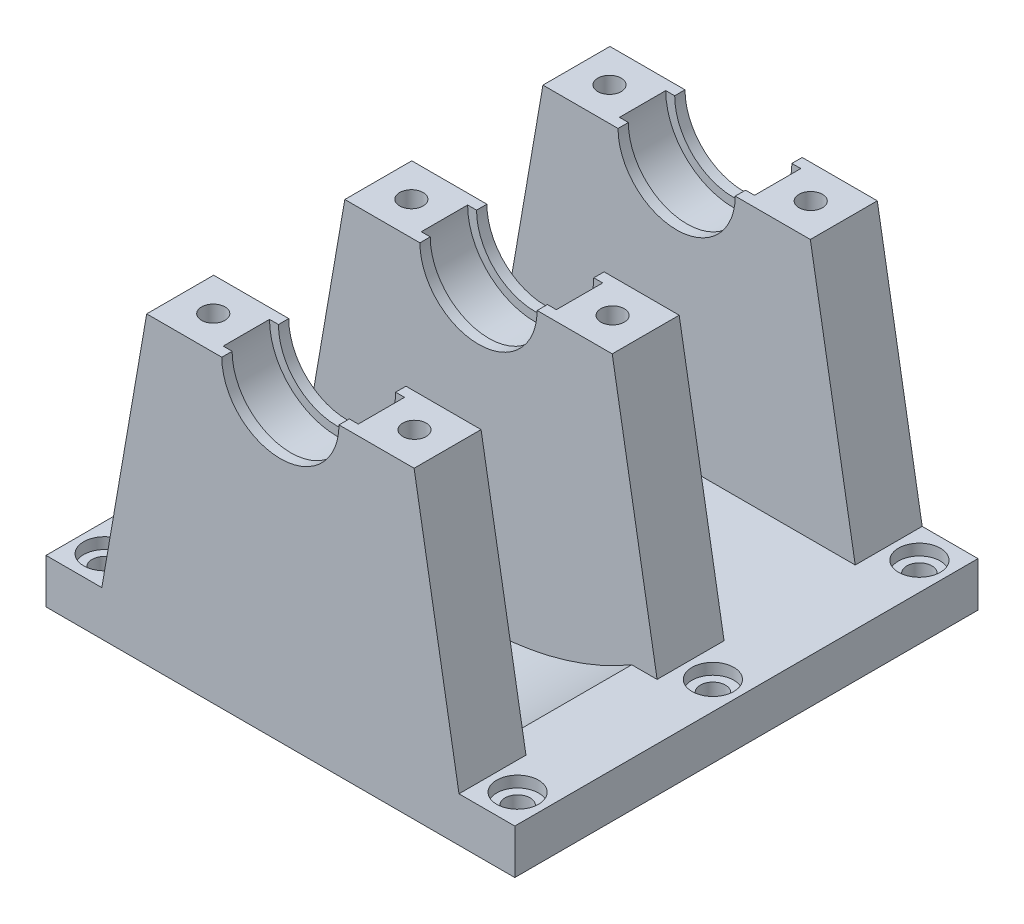
SolidWorks part; units mm, degrees
material "PET"
ref_plane "Piano frontale" through (0, 0, 0) normal (0, 0, 1) x (1, 0, 0)
ref_plane "Piano superiore" through (0, 0, 0) normal (0, 1, 0) x (1, 0, 0)
ref_plane "Piano destro" through (0, 0, 0) normal (1, 0, 0) x (0, 0, -1)
sketch "Schizzo1" plane through (0, 0, 0) normal (0, 0, 1) x (1, 0, 0)
  line L0 (-42, -54.5) -> (42, -54.5)
  line L1 (21, -17.1) -> (-21, -17.1)
  line L2 (21, -17.1) -> (21, 17.1)
  line L3 (21, 17.1) -> (-21, 17.1)
  line L4 (-21, -17.1) -> (-21, 17.1)
  line L5 (21, -17.1) -> (-21, 17.1) construction
  line L6 (21, 17.1) -> (-21, -17.1) construction
  line L7 (-42, -54.5) -> (-42, -46.5)
  line L8 (-42, -46.5) -> (-32, -46.5)
  line L9 (-32, -46.5) -> (-21, 17.1)
  line L10 (42, -54.5) -> (42, -46.5)
  line L11 (42, -46.5) -> (32, -46.5)
  line L12 (32, -46.5) -> (21, 17.1)
  line L13 (-23.9575, 0) -> (23.9575, 0)
  circle A0 centre (0, 0) radius 12.1
  point P9 (0, -54.5)
  dimension "D1" = 24.2
  dimension "D2" = 42
  dimension "D3" = 17.1
  dimension "D4" = 54.5
  dimension "D5" = 84
  dimension "D6" = 8
  dimension "D7" = 10
extrude "Estrusione-Estrusione1" add sketch "Schizzo1" along normal blind 12 contours A0 L13 L4 L1 L2 | L13 L9 L8 L7 L0 L10 L11 L12 L2 L1 L4
sketch "Schizzo2" plane through (0, 0, 12) normal (0, 0, 1) x (1, 0, 0)
  line L0 (-12.1, 0) -> (12.1, 0)
  circle A0 centre (0, 0) radius 10.5
  arc A1 (-12.1, 0) -> (12.1, 0) centre (0, 0) ccw construction
  arc A2 (-12.1, 0) -> (12.1, 0) centre (0, 0) ccw
  arc M11 (12.1, 0) -> (-12.1, 0) centre (0, 0) cw
  dimension "D1" = 21
extrude "Estrusione-Estrusione2" add sketch "Schizzo2" against normal blind 1.85 contours A0 L0 M11
sketch "Schizzo3" plane through (0, 0, 0) normal (0, 0, -1) x (-1, 0, 0)
  line L0 (-12.1, 0) -> (12.1, 0)
  circle A0 centre (0, 0) radius 10.5
  arc A1 (-12.1, 0) -> (12.1, 0) centre (0, 0) ccw construction
  arc A2 (-12.1, 0) -> (12.1, 0) centre (0, 0) ccw
  arc M3 (12.1, 0) -> (-12.1, 0) centre (0, 0) cw
  dimension "D1" = 21
extrude "Estrusione-Estrusione3" add sketch "Schizzo3" against normal blind 1.85 contours A0 L0 M3
sketch "Schizzo4" plane through (0, 0, 0) normal (0, 0, -1) x (-1, 0, 0)
  line L0 (-32, -46.5) -> (32, -46.5)
  line L9 (23.9575, 0) -> (10.5, 0)
  line L10 (-10.5, 0) -> (-23.9575, 0)
  line L11 (-23.9575, 0) -> (-32, -46.5)
  line L12 (-32, -46.5) -> (-42, -46.5)
  line L13 (-42, -46.5) -> (-42, -54.5)
  line L14 (-42, -54.5) -> (42, -54.5)
  line L15 (42, -54.5) -> (42, -46.5)
  line L16 (42, -46.5) -> (32, -46.5)
  line L17 (32, -46.5) -> (23.9575, 0)
  line L18 (23.9575, 0) -> (10.5, 0)
  line L19 (-10.5, 0) -> (-23.9575, 0)
  line L20 (-23.9575, 0) -> (-32, -46.5)
  line L21 (-32, -46.5) -> (-42, -46.5)
  line L22 (-42, -46.5) -> (-42, -54.5)
  line L23 (-42, -54.5) -> (42, -54.5)
  line L24 (42, -54.5) -> (42, -46.5)
  line L25 (42, -46.5) -> (32, -46.5)
  line L26 (32, -46.5) -> (23.9575, 0)
  circle A0 centre (0, 0) radius 54
  arc A1 (-10.5, 0) -> (10.5, 0) centre (0, 0) ccw
  arc A2 (-10.5, 0) -> (10.5, 0) centre (0, 0) ccw
  line M15 (-32, -46.5) -> (-42, -46.5)
  line M16 (-42, -46.5) -> (-42, -54.5)
  line M17 (-42, -54.5) -> (42, -54.5)
  line M18 (42, -54.5) -> (42, -46.5)
  line M19 (42, -46.5) -> (32, -46.5)
  dimension "D2" = 108
  dimension "D1" = 0
extrude "Estrusione-Estrusione4" add sketch "Schizzo4" along normal blind 23.5 contours A0 L0 M15 M16 M17 M18 M19
sketch "Schizzo5" plane through (0, 0, -23.5) normal (0, 0, -1) x (-1, 0, 0)
  line L9 (23.9575, 0) -> (10.5, 0)
  line L10 (32, -46.5) -> (23.9575, 0)
  line L11 (42, -46.5) -> (32, -46.5)
  line L12 (42, -54.5) -> (42, -46.5)
  line L13 (-42, -54.5) -> (42, -54.5)
  line L14 (-42, -46.5) -> (-42, -54.5)
  line L15 (-32, -46.5) -> (-42, -46.5)
  line L16 (-23.9575, 0) -> (-32, -46.5)
  line L17 (-10.5, 0) -> (-23.9575, 0)
  line L18 (23.9575, 0) -> (10.5, 0)
  line L19 (32, -46.5) -> (23.9575, 0)
  line L20 (42, -46.5) -> (32, -46.5)
  line L21 (42, -54.5) -> (42, -46.5)
  line L22 (-42, -54.5) -> (42, -54.5)
  line L23 (-42, -46.5) -> (-42, -54.5)
  line L24 (-32, -46.5) -> (-42, -46.5)
  line L25 (-23.9575, 0) -> (-32, -46.5)
  line L26 (-10.5, 0) -> (-23.9575, 0)
  arc A1 (-10.5, 0) -> (10.5, 0) centre (0, 0) ccw
  arc A2 (-10.5, 0) -> (10.5, 0) centre (0, 0) ccw
  dimension "D1" = 0
extrude "Estrusione-Estrusione5" add sketch "Schizzo5" along normal blind 1.85
sketch "Schizzo6" plane through (0, 0, -25.35) normal (0, 0, -1) x (-1, 0, 0)
  line L2 (-10.5, 0) -> (-12.1, 0)
  line L3 (12.1, 0) -> (10.5, 0)
  line L4 (-10.5, 0) -> (-12.1, 0)
  line L5 (12.1, 0) -> (10.5, 0)
  line L13 (-10.5, 0) -> (-23.9575, 0)
  line L14 (-23.9575, 0) -> (-32, -46.5)
  line L15 (-32, -46.5) -> (-42, -46.5)
  line L16 (-42, -46.5) -> (-42, -54.5)
  line L17 (-42, -54.5) -> (42, -54.5)
  line L18 (42, -54.5) -> (42, -46.5)
  line L19 (42, -46.5) -> (32, -46.5)
  line L20 (32, -46.5) -> (23.9575, 0)
  line L21 (23.9575, 0) -> (10.5, 0)
  line L22 (-10.5, 0) -> (-23.9575, 0)
  line L23 (-23.9575, 0) -> (-32, -46.5)
  line L24 (-32, -46.5) -> (-42, -46.5)
  line L25 (-42, -46.5) -> (-42, -54.5)
  line L26 (-42, -54.5) -> (42, -54.5)
  line L27 (42, -54.5) -> (42, -46.5)
  line L28 (42, -46.5) -> (32, -46.5)
  line L29 (32, -46.5) -> (23.9575, 0)
  line L30 (23.9575, 0) -> (10.5, 0)
  arc A1 (-10.5, 0) -> (10.5, 0) centre (0, 0) ccw
  arc A2 (-10.5, 0) -> (10.5, 0) centre (0, 0) ccw
  arc A3 (-12.1, 0) -> (12.1, 0) centre (0, 0) ccw
  arc A4 (-10.5, 0) -> (10.5, 0) centre (0, 0) ccw
  arc A5 (-12.1, 0) -> (12.1, 0) centre (0, 0) ccw
  arc A6 (-10.5, 0) -> (10.5, 0) centre (0, 0) ccw
  line M16 (-10.5, 0) -> (-23.9575, 0)
  line M17 (-23.9575, 0) -> (-32, -46.5)
  line M18 (-32, -46.5) -> (-42, -46.5)
  line M19 (-42, -46.5) -> (-42, -54.5)
  line M20 (-42, -54.5) -> (42, -54.5)
  line M21 (42, -54.5) -> (42, -46.5)
  line M22 (42, -46.5) -> (32, -46.5)
  line M23 (32, -46.5) -> (23.9575, 0)
  line M24 (23.9575, 0) -> (10.5, 0)
  dimension "D1" = 0
  dimension "D2" = 0
extrude "Estrusione-Estrusione6" add sketch "Schizzo6" along normal blind 8.3 contours A5 M16 M17 M18 M19 M20 M21 M22 M23 M24
sketch "Schizzo7" plane through (0, 0, -33.65) normal (0, 0, -1) x (-1, 0, 0)
  line L9 (23.9575, 0) -> (10.5, 0)
  line L10 (32, -46.5) -> (23.9575, 0)
  line L11 (42, -46.5) -> (32, -46.5)
  line L12 (42, -54.5) -> (42, -46.5)
  line L13 (-42, -54.5) -> (42, -54.5)
  line L14 (-42, -46.5) -> (-42, -54.5)
  line L15 (-32, -46.5) -> (-42, -46.5)
  line L16 (-23.9575, 0) -> (-32, -46.5)
  line L17 (-10.5, 0) -> (-23.9575, 0)
  line L18 (23.9575, 0) -> (10.5, 0)
  line L19 (32, -46.5) -> (23.9575, 0)
  line L20 (42, -46.5) -> (32, -46.5)
  line L21 (42, -54.5) -> (42, -46.5)
  line L22 (-42, -54.5) -> (42, -54.5)
  line L23 (-42, -46.5) -> (-42, -54.5)
  line L24 (-32, -46.5) -> (-42, -46.5)
  line L25 (-23.9575, 0) -> (-32, -46.5)
  line L26 (-10.5, 0) -> (-23.9575, 0)
  arc A1 (-10.5, 0) -> (10.5, 0) centre (0, 0) ccw
  arc A2 (-10.5, 0) -> (10.5, 0) centre (0, 0) ccw
  dimension "D1" = 0
extrude "Estrusione-Estrusione7" add sketch "Schizzo7" along normal blind 1.85
sketch "Schizzo8" plane through (0, 0, -35.5) normal (0, 0, -1) x (-1, 0, 0)
  line L0 (-32, -46.5) -> (32, -46.5)
  line L9 (-10.5, 0) -> (-23.9575, 0)
  line L10 (-23.9575, 0) -> (-32, -46.5)
  line L11 (-32, -46.5) -> (-42, -46.5)
  line L12 (-42, -46.5) -> (-42, -54.5)
  line L13 (-42, -54.5) -> (42, -54.5)
  line L14 (42, -54.5) -> (42, -46.5)
  line L15 (42, -46.5) -> (32, -46.5)
  line L16 (32, -46.5) -> (23.9575, 0)
  line L17 (23.9575, 0) -> (10.5, 0)
  line L18 (-10.5, 0) -> (-23.9575, 0)
  line L19 (-23.9575, 0) -> (-32, -46.5)
  line L20 (-32, -46.5) -> (-42, -46.5)
  line L21 (-42, -46.5) -> (-42, -54.5)
  line L22 (-42, -54.5) -> (42, -54.5)
  line L23 (42, -54.5) -> (42, -46.5)
  line L24 (42, -46.5) -> (32, -46.5)
  line L25 (32, -46.5) -> (23.9575, 0)
  line L26 (23.9575, 0) -> (10.5, 0)
  arc A1 (-10.5, 0) -> (10.5, 0) centre (0, 0) ccw
  arc A2 (-10.5, 0) -> (10.5, 0) centre (0, 0) ccw
  line M14 (-32, -46.5) -> (-42, -46.5)
  line M15 (-42, -46.5) -> (-42, -54.5)
  line M16 (-42, -54.5) -> (42, -54.5)
  line M17 (42, -54.5) -> (42, -46.5)
  line M18 (42, -46.5) -> (32, -46.5)
  dimension "D1" = 0
extrude "Estrusione-Estrusione8" add sketch "Schizzo8" along normal blind 23.5 contours L0 M14 M15 M16 M17 M18
sketch "Schizzo9" plane through (0, 0, -59) normal (0, 0, -1) x (-1, 0, 0)
  line L9 (23.9575, 0) -> (10.5, 0)
  line L10 (32, -46.5) -> (23.9575, 0)
  line L11 (42, -46.5) -> (32, -46.5)
  line L12 (42, -54.5) -> (42, -46.5)
  line L13 (-42, -54.5) -> (42, -54.5)
  line L14 (-42, -46.5) -> (-42, -54.5)
  line L15 (-32, -46.5) -> (-42, -46.5)
  line L16 (-23.9575, 0) -> (-32, -46.5)
  line L17 (-10.5, 0) -> (-23.9575, 0)
  line L18 (23.9575, 0) -> (10.5, 0)
  line L19 (32, -46.5) -> (23.9575, 0)
  line L20 (42, -46.5) -> (32, -46.5)
  line L21 (42, -54.5) -> (42, -46.5)
  line L22 (-42, -54.5) -> (42, -54.5)
  line L23 (-42, -46.5) -> (-42, -54.5)
  line L24 (-32, -46.5) -> (-42, -46.5)
  line L25 (-23.9575, 0) -> (-32, -46.5)
  line L26 (-10.5, 0) -> (-23.9575, 0)
  arc A1 (-10.5, 0) -> (10.5, 0) centre (0, 0) ccw
  arc A2 (-10.5, 0) -> (10.5, 0) centre (0, 0) ccw
  dimension "D1" = 0
extrude "Estrusione-Estrusione9" add sketch "Schizzo9" along normal blind 1.85
sketch "Schizzo10" plane through (0, 0, -60.85) normal (0, 0, -1) x (-1, 0, 0)
  line L0 (-10.5, 0) -> (-23.9575, 0) construction
  line L1 (-23.9575, 0) -> (-32, -46.5) construction
  line L2 (-32, -46.5) -> (-42, -46.5) construction
  line L3 (-42, -46.5) -> (-42, -54.5) construction
  line L4 (-42, -54.5) -> (42, -54.5) construction
  line L5 (42, -54.5) -> (42, -46.5) construction
  line L6 (42, -46.5) -> (32, -46.5) construction
  line L7 (32, -46.5) -> (23.9575, 0) construction
  line L8 (23.9575, 0) -> (10.5, 0) construction
  line L9 (-10.5, 0) -> (-12.1, 0) construction
  line L10 (12.1, 0) -> (10.5, 0) construction
  line L11 (-10.5, 0) -> (-23.9575, 0)
  line L12 (-23.9575, 0) -> (-32, -46.5)
  line L13 (-32, -46.5) -> (-42, -46.5)
  line L14 (-42, -46.5) -> (-42, -54.5)
  line L15 (-42, -54.5) -> (42, -54.5)
  line L16 (42, -54.5) -> (42, -46.5)
  line L17 (42, -46.5) -> (32, -46.5)
  line L18 (32, -46.5) -> (23.9575, 0)
  line L19 (23.9575, 0) -> (10.5, 0)
  line L20 (-10.5, 0) -> (-12.1, 0)
  line L21 (12.1, 0) -> (10.5, 0)
  arc A0 (-10.5, 0) -> (10.5, 0) centre (0, 0) ccw construction
  arc A1 (-12.1, 0) -> (12.1, 0) centre (0, 0) ccw construction
  arc A2 (-10.5, 0) -> (10.5, 0) centre (0, 0) ccw construction
  arc A3 (-10.5, 0) -> (10.5, 0) centre (0, 0) ccw
  arc A4 (-12.1, 0) -> (12.1, 0) centre (0, 0) ccw
  arc A5 (-10.5, 0) -> (10.5, 0) centre (0, 0) ccw
  line M3 (-23.9575, 0) -> (-32, -46.5)
  line M4 (-32, -46.5) -> (-42, -46.5)
  line M5 (-42, -46.5) -> (-42, -54.5)
  line M6 (-42, -54.5) -> (42, -54.5)
  line M7 (42, -54.5) -> (42, -46.5)
  line M8 (42, -46.5) -> (32, -46.5)
  line M9 (32, -46.5) -> (23.9575, 0)
  line M10 (23.9575, 0) -> (10.5, 0)
extrude "Estrusione-Estrusione10" add sketch "Schizzo10" along normal blind 8.3 contours A4 L11 M3 M4 M5 M6 M7 M8 M9 M10
sketch "Schizzo11" plane through (0, 0, -69.15) normal (0, 0, -1) x (-1, 0, 0)
  line L9 (23.9575, 0) -> (10.5, 0)
  line L10 (32, -46.5) -> (23.9575, 0)
  line L11 (42, -46.5) -> (32, -46.5)
  line L12 (42, -54.5) -> (42, -46.5)
  line L13 (-42, -54.5) -> (42, -54.5)
  line L14 (-42, -46.5) -> (-42, -54.5)
  line L15 (-32, -46.5) -> (-42, -46.5)
  line L16 (-23.9575, 0) -> (-32, -46.5)
  line L17 (-10.5, 0) -> (-23.9575, 0)
  line L18 (23.9575, 0) -> (10.5, 0)
  line L19 (32, -46.5) -> (23.9575, 0)
  line L20 (42, -46.5) -> (32, -46.5)
  line L21 (42, -54.5) -> (42, -46.5)
  line L22 (-42, -54.5) -> (42, -54.5)
  line L23 (-42, -46.5) -> (-42, -54.5)
  line L24 (-32, -46.5) -> (-42, -46.5)
  line L25 (-23.9575, 0) -> (-32, -46.5)
  line L26 (-10.5, 0) -> (-23.9575, 0)
  arc A1 (-10.5, 0) -> (10.5, 0) centre (0, 0) ccw
  arc A2 (-10.5, 0) -> (10.5, 0) centre (0, 0) ccw
  dimension "D1" = 0
extrude "Estrusione-Estrusione11" add sketch "Schizzo11" along normal blind 1.85 contours L18 A2 L26 L25 L24 L23 L22 L21 L20 L19
sketch "Schizzo12" plane through (0, -46.5, 0) normal (0, 1, 0) x (1, 0, 0)
  line L0 (37, -12) -> (37, 71) construction
  line L1 (42, -12) -> (32, -12) construction
  line L2 (32, 71) -> (42, 71) construction
  line L3 (-37, -12) -> (-37, 71) construction
  line L4 (-42, -12) -> (-32, -12) construction
  line L5 (-42, 71) -> (-32, 71) construction
  circle A0 centre (37, -6.5) radius 2.25
  circle A1 centre (37, 28.5) radius 2.25
  circle A2 centre (37, 65.5) radius 2.25
  circle A3 centre (-37, -6.5) radius 2.25
  circle A4 centre (-37, 28.5) radius 2.25
  circle A5 centre (-37, 65.5) radius 2.25
  dimension "D1" = 4.5
  dimension "D2" = 5.5
  dimension "D3" = 5.5
  dimension "D4" = 40.5
  dimension "D5" = 40.5
  dimension "D6" = 77.5
  dimension "D7" = 77.5
extrude "Taglio-Estrusione1" cut sketch "Schizzo12" against normal through all
sketch "Schizzo13" plane through (0, 0, 0) normal (0, 1, 0) x (1, 0, 0)
  line L0 (12.1, 29.5) -> (23.9575, 29.5) construction
  line L1 (12.1, 33.65) -> (12.1, 25.35) construction
  line L2 (23.9575, 35.5) -> (23.9575, 23.5) construction
  line L3 (-12.1, 29.5) -> (-23.9575, 29.5) construction
  line L4 (-12.1, 33.65) -> (-12.1, 25.35) construction
  line L5 (-23.9575, 35.5) -> (-23.9575, 23.5) construction
  line L6 (23.9575, 65) -> (12.1, 65) construction
  line L7 (23.9575, 71) -> (23.9575, 59) construction
  line L8 (12.1, 69.15) -> (12.1, 60.85) construction
  line L9 (-12.1, 65) -> (-23.9575, 65) construction
  line L10 (-12.1, 69.15) -> (-12.1, 60.85) construction
  line L11 (-23.9575, 71) -> (-23.9575, 59) construction
  line L12 (23.9575, -6) -> (12.1, -6) construction
  line L13 (23.9575, -12) -> (23.9575, 0) construction
  line L14 (12.1, -10.15) -> (12.1, -1.85) construction
  line L15 (-12.1, -6) -> (-23.9575, -6) construction
  line L16 (-12.1, -10.15) -> (-12.1, -1.85) construction
  line L17 (-23.9575, -12) -> (-23.9575, 0) construction
  circle A0 centre (18.0288, -6) radius 2.1
  circle A1 centre (-18.0288, -6) radius 2.1
  circle A2 centre (18.0288, 29.5) radius 2.1
  circle A3 centre (-18.0288, 29.5) radius 2.1
  circle A4 centre (18.0288, 65) radius 2.1
  circle A5 centre (-18.0288, 65) radius 2.1
  dimension "D1" = 4.2
extrude "Taglio-Estrusione2" cut sketch "Schizzo13" against normal blind 6
sketch "Schizzo15" plane through (0, -6, 0) normal (0, 1, 0) x (1, 0, 0)
  circle A0 centre (-18.0288, 65) radius 2.1 construction
  circle A1 centre (18.0288, 65) radius 2.1 construction
  circle A2 centre (18.0288, 29.5) radius 2.1 construction
  circle A3 centre (-18.0288, 29.5) radius 2.1 construction
  circle A4 centre (-18.0288, -6) radius 2.1 construction
  circle A5 centre (18.0288, -6) radius 2.1 construction
  circle A6 centre (-18.0288, 65) radius 2.1
  circle A7 centre (18.0288, 65) radius 2.1
  circle A8 centre (18.0288, 29.5) radius 2.1
  circle A9 centre (-18.0288, 29.5) radius 2.1
  circle A10 centre (-18.0288, -6) radius 2.1
  circle A11 centre (18.0288, -6) radius 2.1
extrude "Taglio-Estrusione4" cut sketch "Schizzo15" against normal blind 5
sketch "Schizzo16" plane through (0, -46.5, 0) normal (0, 1, 0) x (1, 0, 0)
  circle A0 centre (37, -6.5) radius 3.75
  circle A1 centre (37, 28.5) radius 3.75
  circle A2 centre (37, 65.5) radius 3.75
  circle A3 centre (-37, 65.5) radius 3.75
  circle A4 centre (-37, 28.5) radius 3.75
  circle A5 centre (-37, -6.5) radius 3.75
  dimension "D1" = 7.5
extrude "Taglio-Estrusione5" cut sketch "Schizzo16" against normal blind 2
